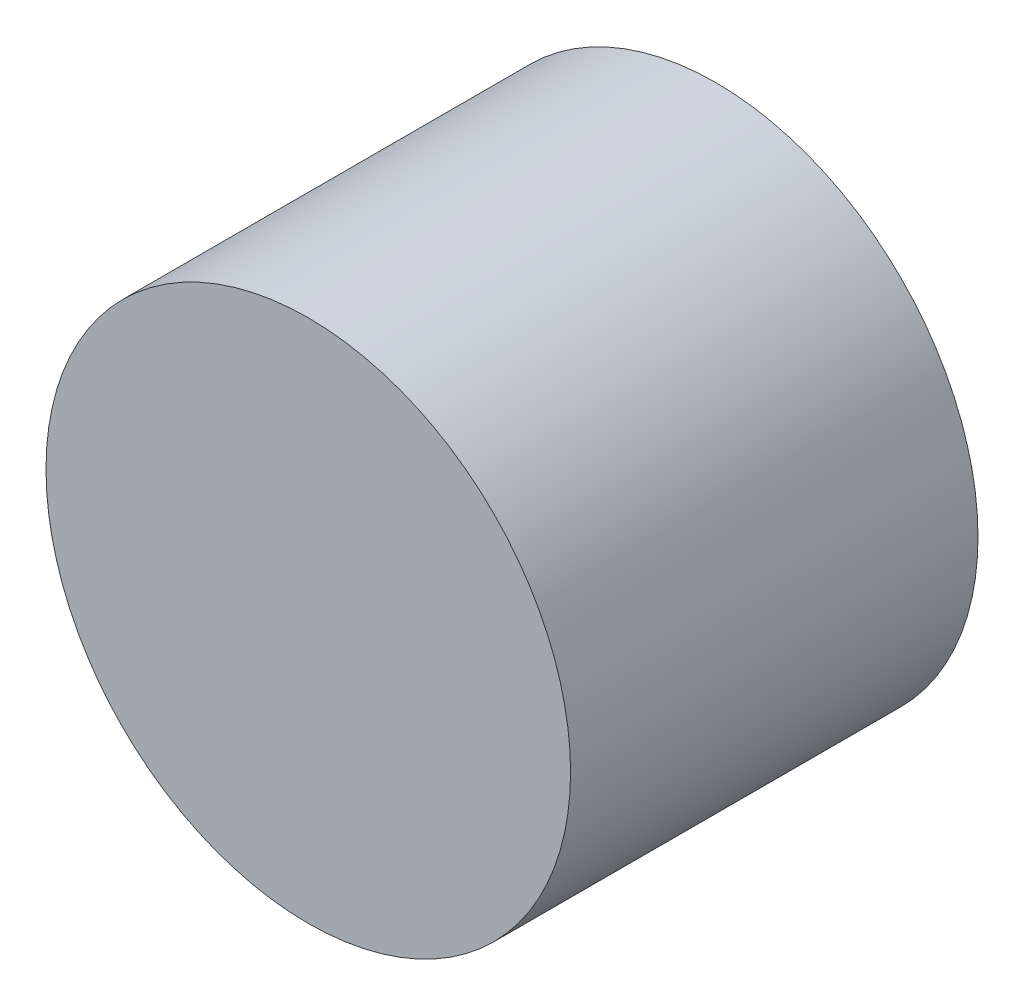
SolidWorks part; units mm, degrees
ref_plane "Front Plane" through (0, 0, 0) normal (0, 0, 1) x (1, 0, 0)
ref_plane "Top Plane" through (0, 0, 0) normal (0, 1, 0) x (1, 0, 0)
ref_plane "Right Plane" through (0, 0, 0) normal (1, 0, 0) x (0, 0, -1)
sketch "Sketch1" plane through (0, 0, 0) normal (0, 0, 1) x (1, 0, 0)
  circle A0 centre (7.125, -5.675) radius 11.475
  dimension "D1" = 22.95
extrude "Boss-Extrude1" add sketch "Sketch1" along normal blind 17.825
